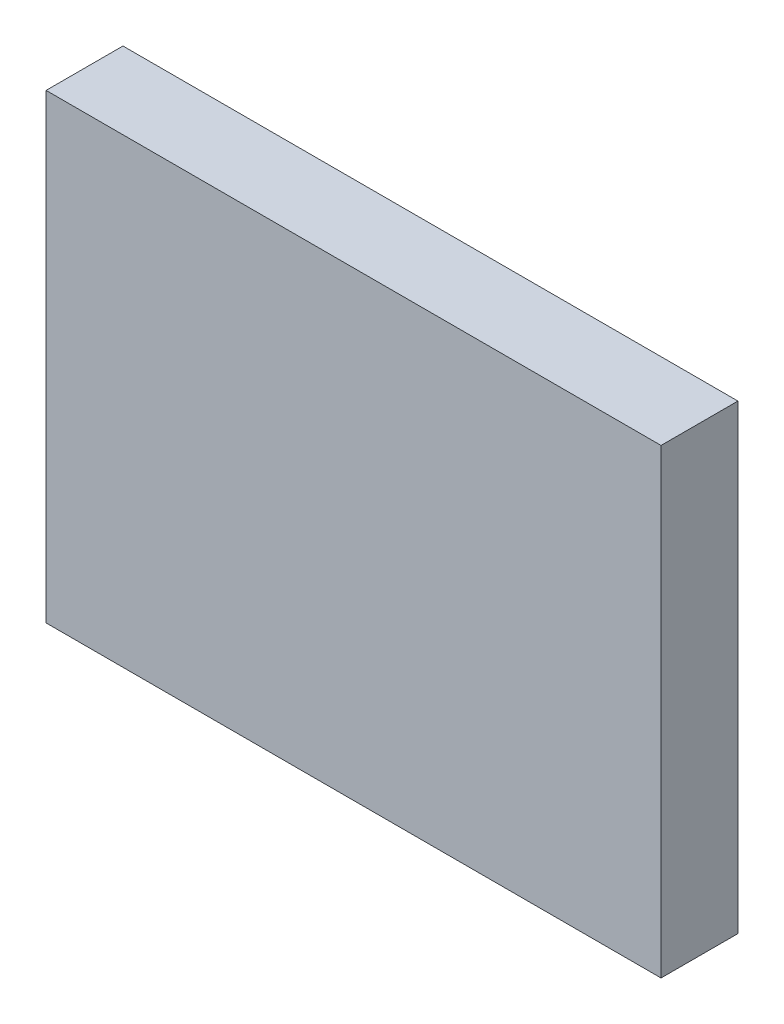
SolidWorks part; units mm, degrees
ref_plane "前视基准面" through (0, 0, 0) normal (0, 0, 1) x (1, 0, 0)
ref_plane "上视基准面" through (0, 0, 0) normal (0, 1, 0) x (1, 0, 0)
ref_plane "右视基准面" through (0, 0, 0) normal (1, 0, 0) x (0, 0, -1)
sketch "草图2" plane through (0, 0, 0) normal (0, 0, 1) x (1, 0, 0)
  line L1 (0, 0) -> (80, 0)
  line L2 (0, 0) -> (0, -60)
  line L3 (0, -60) -> (80, -60)
  line L4 (80, 0) -> (80, -60)
  dimension "D1" = 80
  dimension "D2" = 60
extrude "凸台-拉伸1" add sketch "草图2" along normal blind 10
